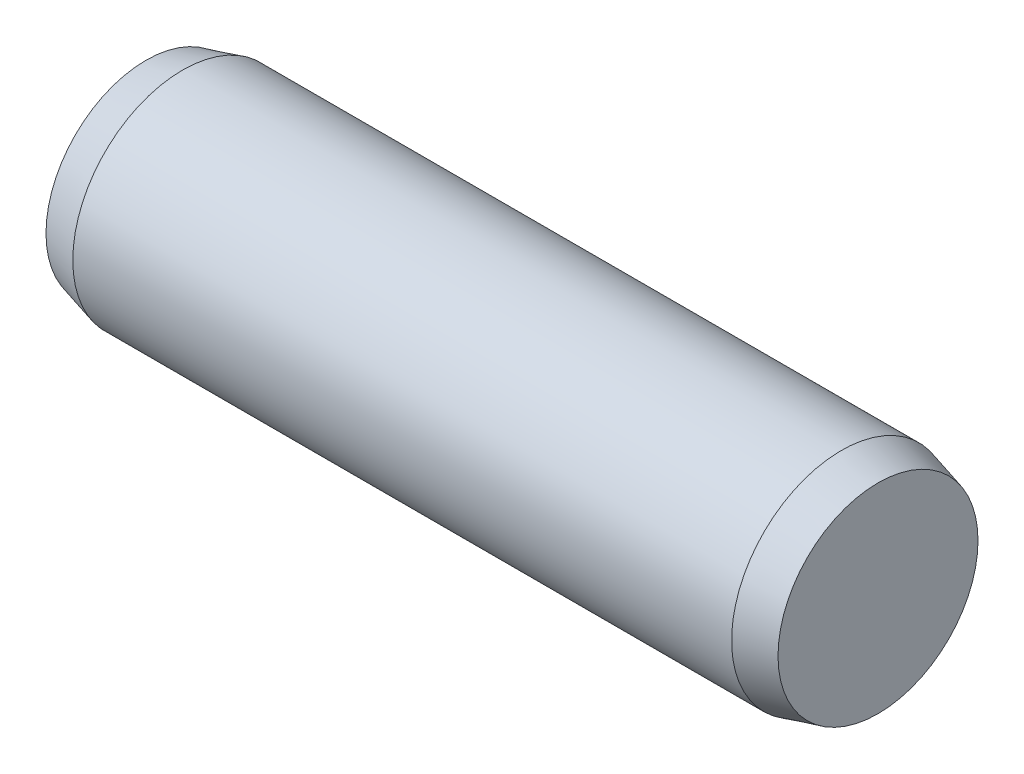
SolidWorks part; units mm, degrees
ref_plane "Front Plane" through (0, 0, 0) normal (0, 0, 1) x (1, 0, 0)
ref_plane "Top Plane" through (0, 0, 0) normal (0, 1, 0) x (1, 0, 0)
ref_plane "Right Plane" through (0, 0, 0) normal (1, 0, 0) x (0, 0, -1)
sketch "Sketch1" plane through (0, 0, 0) normal (0, 0, 1) x (1, 0, 0)
  line L0 (-4.5, 0) -> (4.5, 0) construction
  line L1 (4.5, 1.5) -> (4.5, -1.5) construction
  line L2 (-4.5, 1.5) -> (-4.5, -1.5) construction
  line L3 (5, 1.5) -> (5, -1.5) construction
  line L4 (-5, 1.5) -> (-5, -1.5) construction
  line L5 (-4.5, 0) -> (-5, 0) construction
  line L6 (4.5, 0) -> (5, 0) construction
  dimension "Dia" = 3
  dimension "C" = 0.5
  dimension "D1" = 0.5
  dimension "Length" = 10
sketch "Sketch2" plane through (0, 0, 0) normal (1, 0, 0) x (0, 0, -1)
  circle A0 centre (0, 0) radius 1.5
extrude "Extrude1" add sketch "Sketch2" against normal up to vertex (4.5 mm away) and the other way up to vertex (4.5 mm away) up to point (-4.5, 1.5, 0) other way up to point (4.5, 1.5, 0)
sketch "Sketch3" plane through (4.5, 0, 0) normal (1, 0, 0) x (0, 0, -1)
  circle A1 centre (0, 0) radius 1.5
  circle A2 centre (0, 0) radius 1.5
  dimension "D1" = 0
extrude "Extrude2" add sketch "Sketch3" along normal up to vertex (0.5 mm away) draft 15 up to point (5, 0, 0)
sketch "Sketch4" plane through (-4.5, 0, 0) normal (-1, 0, 0) x (0, 0, 1)
  circle A1 centre (0, 0) radius 1.5
  circle A2 centre (0, 0) radius 1.5
  dimension "D1" = 0
extrude "Extrude3" add sketch "Sketch4" along normal up to vertex (0.5 mm away) draft 15 up to point (-5, 0, 0)
equation "\"D1@Sketch1\" = \"C@Sketch1\""
